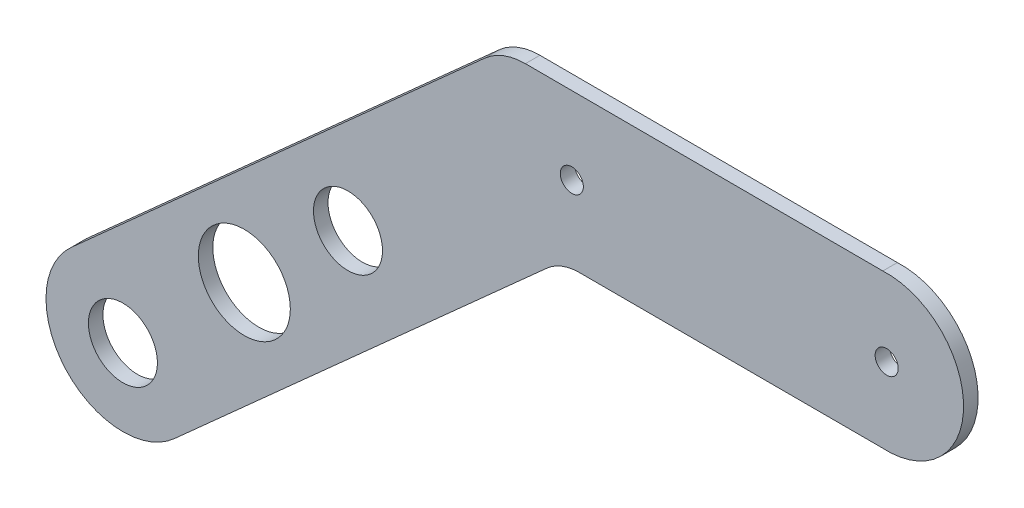
SolidWorks part; units mm, degrees
ref_plane "Alzado" through (0, 0, 0) normal (0, 0, 1) x (1, 0, 0)
ref_plane "Planta" through (0, 0, 0) normal (0, 1, 0) x (1, 0, 0)
ref_plane "Vista lateral" through (0, 0, 0) normal (1, 0, 0) x (0, 0, -1)
sketch "Croquis1" plane through (0, 0, 0) normal (0, 0, 1) x (1, 0, 0)
  line L0 (-83.6308, -69.8869) -> (26.3692, 0.1131) construction
  line L1 (26.3692, 0.1131) -> (26.3692, -69.8869) construction
  line L2 (26.3692, -69.8869) -> (-83.6308, -69.8869) construction
  line L3 (-115.0605, 18.9563) -> (41.5293, 169.8564) construction
  line L9 (41.5293, 169.8564) -> (200.2793, 169.8564) construction
  line L10 (41.5293, 201.9303) -> (198.6879, 201.5665)
  line L11 (65.7504, 138.3699) -> (198.2576, 138.1708)
  line L12 (-136.2507, 42.6003) -> (41.5293, 201.9303)
  line L14 (-93.6274, -4.4677) -> (65.7504, 138.3699)
  line L15 (-115.0605, 18.9563) -> (-22.1304, 105.5184) construction
  circle A0 centre (-138.0898, -66.9091) radius 31.75 construction
  circle A1 centre (-115.0605, 18.9563) radius 57.15 construction
  circle A2 centre (-115.0605, 18.9563) radius 14.25
  circle A5 centre (-22.1304, 105.5184) radius 14.25
  circle A6 centre (-22.1304, 105.5184) radius 57.15 construction
  circle A12 centre (200.2793, 169.8564) radius 4.7625
  circle A13 centre (70.2793, 169.8564) radius 4.7625
  arc A14 (198.2576, 138.1708) -> (198.6879, 201.5665) centre (200.2793, 169.8564) ccw
  arc A15 (-136.2507, 42.6003) -> (-93.6274, -4.4677) centre (-115.0605, 18.9563) ccw
  circle A17 centre (-64.9368, 65.6453) radius 19
  point P9 (-66.0376, 49.2523)
  point P15 (-33.2483, 59.277)
  dimension "D1" = 114.3
  dimension "D2" = 63.5
  dimension "D4" = 28.5
  dimension "D6" = 110
  dimension "D5" = 63.5
  dimension "D9" = 127
  dimension "D10" = 29.3101
  dimension "D11" = 222
  dimension "D14" = 9.525
  dimension "D15" = 38
  dimension "D8" = 63.5
  dimension "D17" = 68.5
  dimension "D3" = 130
  dimension "D7" = 70
  dimension "D12" = 157.1586
  dimension "D13" = 158.75
  dimension "D16" = 238.7296
extrude "Saliente-Extruir1" add sketch "Croquis1" along normal blind 6
fillet "Redondeo1" radius 25 1 edges at (41.5293, 201.9303, 3)
fillet "Redondeo2" radius 20 1 edges at (65.7504, 138.3699, 3)
